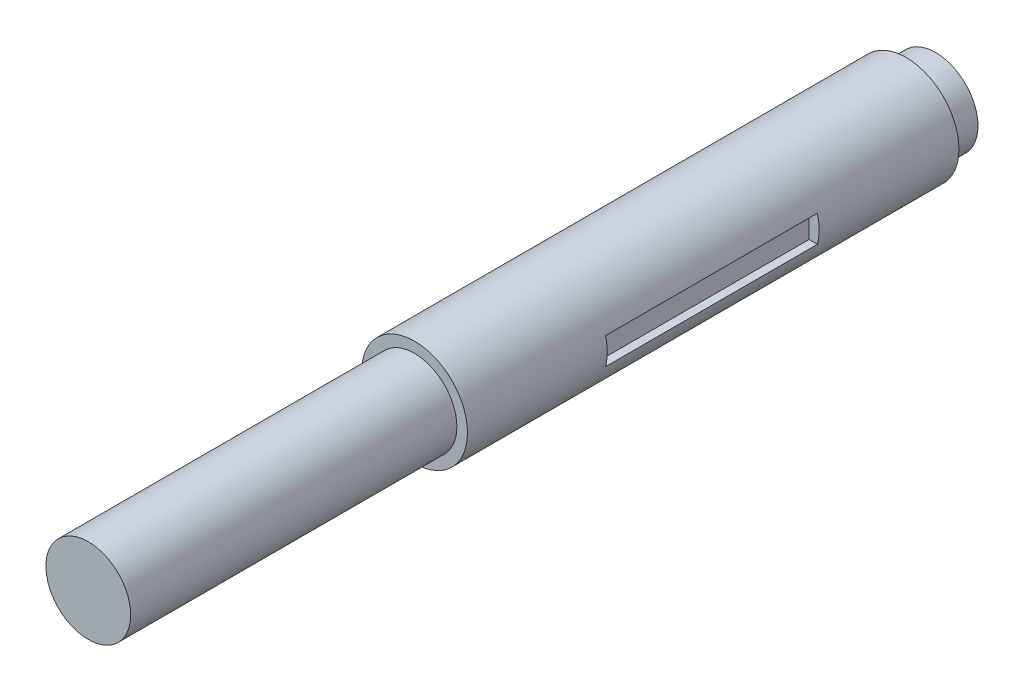
SolidWorks part; units mm, degrees
ref_plane "Front Plane" through (0, 0, 0) normal (0, 0, 1) x (1, 0, 0)
ref_plane "Top Plane" through (0, 0, 0) normal (0, 1, 0) x (1, 0, 0)
ref_plane "Right Plane" through (0, 0, 0) normal (1, 0, 0) x (0, 0, -1)
sketch "Sketch1" plane through (0, 0, 0) normal (0, 0, 1) x (1, 0, 0)
  circle A0 centre (0, 0) radius 12.5
extrude "Boss-Extrude1" add sketch "Sketch1" along normal blind 116 contours A0
sketch "Sketch2" plane through (0, 0, 116) normal (0, 0, 1) x (1, 0, 0)
  circle A0 centre (0, 0) radius 10
sketch "Sketch3" plane through (0, 0, 0) normal (0, 0, -1) x (-1, 0, 0)
  circle A0 centre (0, 0) radius 10
extrude "Boss-Extrude2" add sketch "Sketch2" along normal blind 7
extrude "Boss-Extrude3" add sketch "Sketch3" along normal blind 7
ref_plane "Plane1" through (12.5, 0, 0) normal (1, 0, 0) x (0, 0, -1)
sketch "Sketch4" plane through (12.5, 0, 0) normal (1, 0, 0) x (0, 0, -1)
  line L0 (-123, 10) -> (-123, -10) construction
  line L1 (-33, 3.175) -> (-83, 3.175)
  line L2 (-33, 3.175) -> (-33, -3.175)
  line L3 (-33, -3.175) -> (-83, -3.175)
  line L4 (-83, 3.175) -> (-83, -3.175)
  line L8 (0, 12.5) -> (-116, 12.5) construction
  dimension "D1" = 40
  dimension "D2" = 50
  dimension "D3" = 6.35
  dimension "D4" = 9.325
extrude "Cut-Extrude1" cut sketch "Sketch4" against normal blind 2.3813
sketch "Sketch6" plane through (0, 0, 123) normal (0, 0, 1) x (1, 0, 0)
  circle A0 centre (0, 0) radius 10
extrude "Boss-Extrude4" add sketch "Sketch6" along normal blind 70
